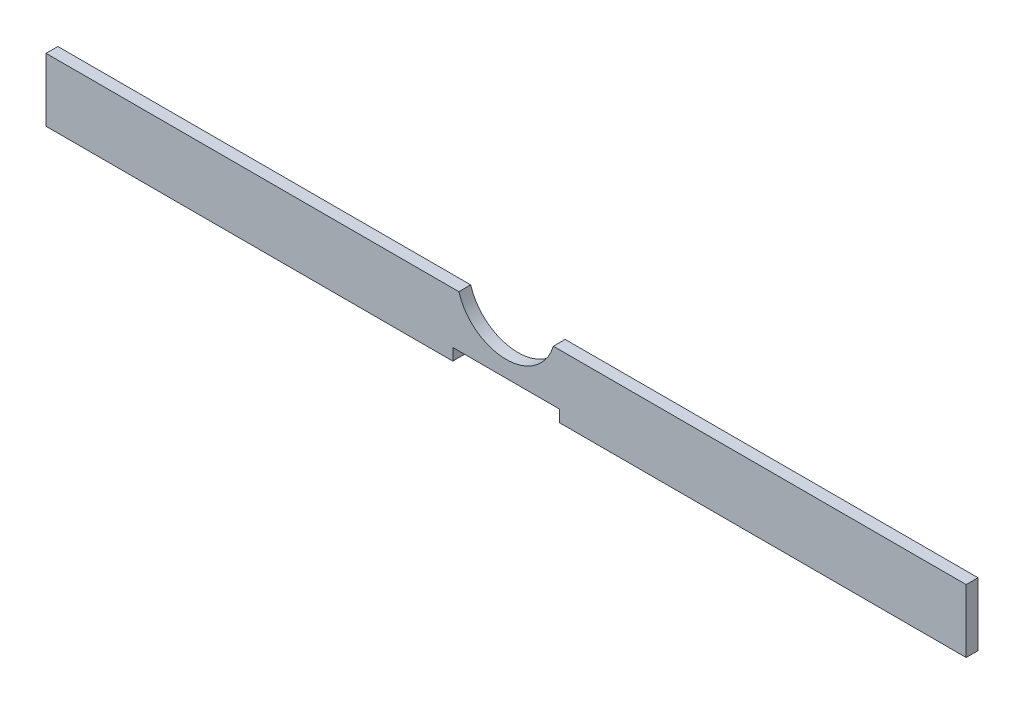
SolidWorks part; units mm, degrees
ref_plane "Přední rovina" through (0, 0, 0) normal (0, 0, 1) x (1, 0, 0)
ref_plane "Horní rovina" through (0, 0, 0) normal (0, 1, 0) x (1, 0, 0)
ref_plane "Pravá rovina" through (0, 0, 0) normal (1, 0, 0) x (0, 0, -1)
sketch "Skica1" plane through (0, 0, 0) normal (0, 0, 1) x (1, 0, 0)
  line L0 (0, 0) -> (0, 43.2556) construction
  line L1 (-116.5, 0) -> (-13.5, 0)
  line L3 (-116.5, 16) -> (-53.5, 16)
  line L4 (116.5, 0) -> (116.5, 16)
  line L5 (-116.5, 0) -> (-116.5, 16)
  line L6 (11.9613, 16) -> (53.5, 16)
  line L7 (53.5, 16) -> (116.5, 16)
  line L15 (-53.5, 16) -> (-11.9613, 16)
  line L16 (13.5, 3) -> (-13.5, 3)
  line L17 (-13.5, 3) -> (-13.5, 0)
  line L18 (13.5, 3) -> (13.5, 0)
  line L19 (13.5, 0) -> (116.5, 0)
  arc A0 (-11.9613, 16) -> (11.9613, 16) centre (0, 19.63) ccw
  point P17 (0, 3)
  dimension "D3" = 19.63
  dimension "D4" = 12.5
  dimension "D1" = 16
  dimension "D2" = 233
  dimension "D5" = 3
  dimension "D6" = 27
extrude "Přidat vysunutím1" add sketch "Skica1" along normal blind 3
